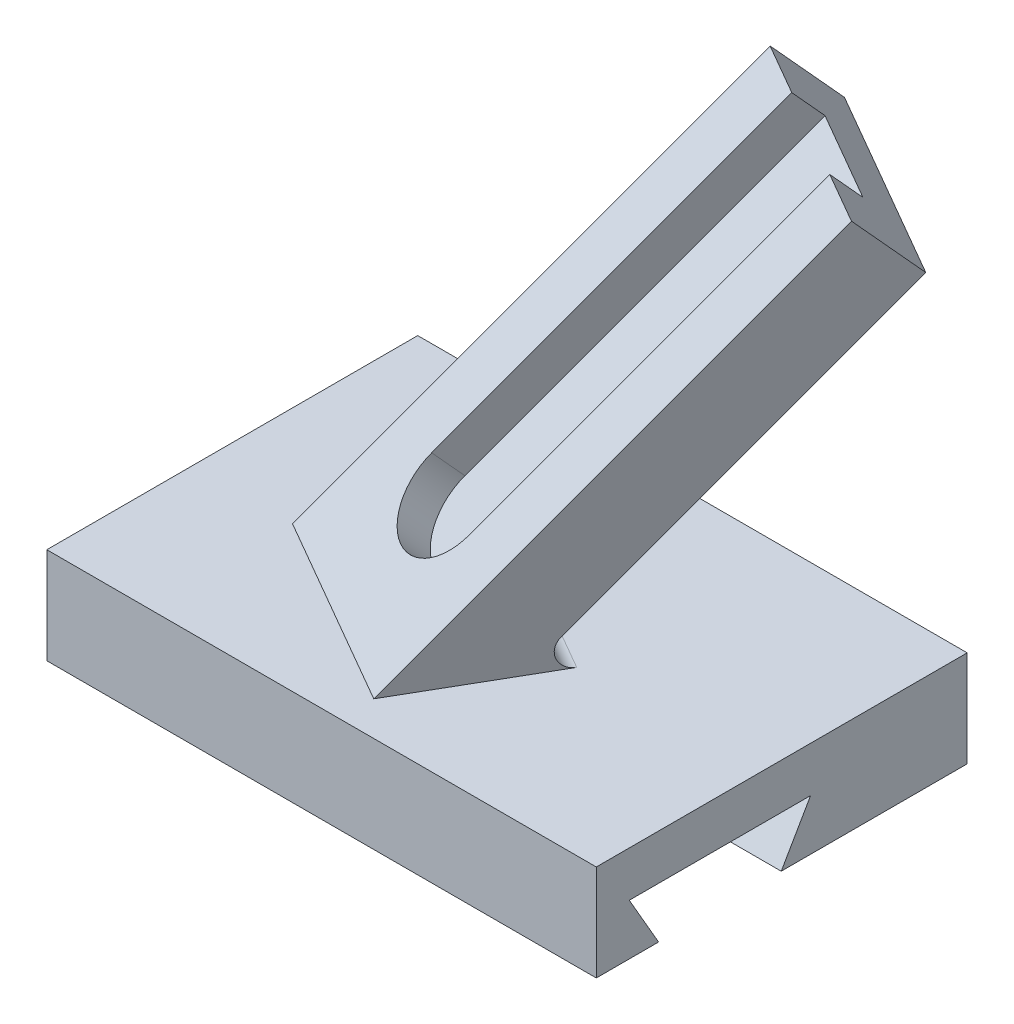
SolidWorks part; units mm, degrees
material "6061 Alloy"
ref_plane "Front Plane" through (0, 0, 0) normal (0, 0, 1) x (1, 0, 0)
ref_plane "Top Plane" through (0, 0, 0) normal (0, 1, 0) x (1, 0, 0)
ref_plane "Right Plane" through (0, 0, 0) normal (1, 0, 0) x (0, 0, -1)
sketch "Croquis1" plane through (0, 0, 0) normal (0, 1, 0) x (1, 0, 0)
  line L1 (0, 0) -> (101.6, 0)
  line L2 (0, 0) -> (0, 68.58)
  line L3 (0, 68.58) -> (101.6, 68.58)
  line L4 (101.6, 0) -> (101.6, 68.58)
  dimension "D1" = 101.6
  dimension "D2" = 68.58
extrude "Saliente-Extruir1" add sketch "Croquis1" along normal blind 17.78
sketch "Croquis2" plane through (0, 17.78, 0) normal (0, 1, 0) x (1, 0, 0)
  line L0 (54.102, 6.35) -> (18.542, 26.8806) construction
  line L1 (101.6, 0) -> (101.6, 68.58) construction
  line L2 (0, 0) -> (101.6, 0) construction
  point P6 (0, 0)
  dimension "D1" = 47.498
  dimension "D2" = 6.35
  dimension "D3" = 30
  dimension "D4" = 35.56
ref_plane "Plano1" through (3.6926, -7.3851, -6.3957) normal (-0.3536, 0.7071, 0.6124) x (-0.866, 0, -0.5)
sketch "Croquis4" plane through (3.6926, -7.3851, -6.3957) normal (-0.3536, 0.7071, 0.6124) x (-0.866, 0, -0.5)
  line L0 (-43.6787, -35.5889) -> (-2.6176, -35.5889)
  line L1 (-2.6176, -35.5889) -> (-2.6176, -127.0289)
  line L2 (-2.6176, -127.0289) -> (-43.6787, -127.0289)
  line L3 (-43.6787, -127.0289) -> (-43.6787, -35.5889)
  dimension "D1" = 91.44
extrude "Saliente-Extruir2" add sketch "Croquis4" against normal blind 14.224
sketch "Croquis5" plane through (3.6926, -7.3851, -6.3957) normal (-0.3536, 0.7071, 0.6124) x (0.9354, 0.2673, 0.2315)
  line L0 (69.4434, 108.8567) -> (43.5226, 45.364) construction
  line L1 (88.451, 101.0969) -> (50.4358, 116.6165) construction
  line L2 (60.5644, 112.4816) -> (78.3225, 105.2319)
  line L3 (78.3225, 105.2319) -> (52.2676, 41.4106)
  line L4 (60.5644, 112.4816) -> (34.5095, 48.6604)
  line L5 (60.5644, 112.4816) -> (34.5095, 48.6604)
  arc A0 (34.5095, 48.6604) -> (52.2676, 41.4106) centre (43.3885, 45.0355) ccw
  point P7 (69.4434, 108.8567)
  dimension "D1" = 68.58
extrude "Cortar-Extruir1" cut sketch "Croquis5" against normal blind 6.35
fillet "Redondeo2" radius 3.048 1 edges at (46.3799, 17.78, -34.0361)
sketch "Croquis6" plane through (101.6, 0, 0) normal (1, 0, 0) x (0, 0, -1)
  line L0 (0, 17.78) -> (0, 0) construction
  line L1 (6.096, 9.398) -> (39.624, 9.398)
  line L2 (0, 0) -> (68.58, 0) construction
  line L3 (6.096, 9.398) -> (11.5219, 0)
  line L4 (11.5219, 0) -> (34.1981, 0)
  line L5 (34.1981, 0) -> (39.624, 9.398)
  point P0 (22.86, 9.398)
  point P6 (22.86, 9.398)
  dimension "D1" = 22.86
  dimension "D2" = 33.528
  dimension "D3" = 9.398
  dimension "D4" = 60
  dimension "D5" = 60
extrude "Cortar-Extruir2" cut sketch "Croquis6" against normal through all
